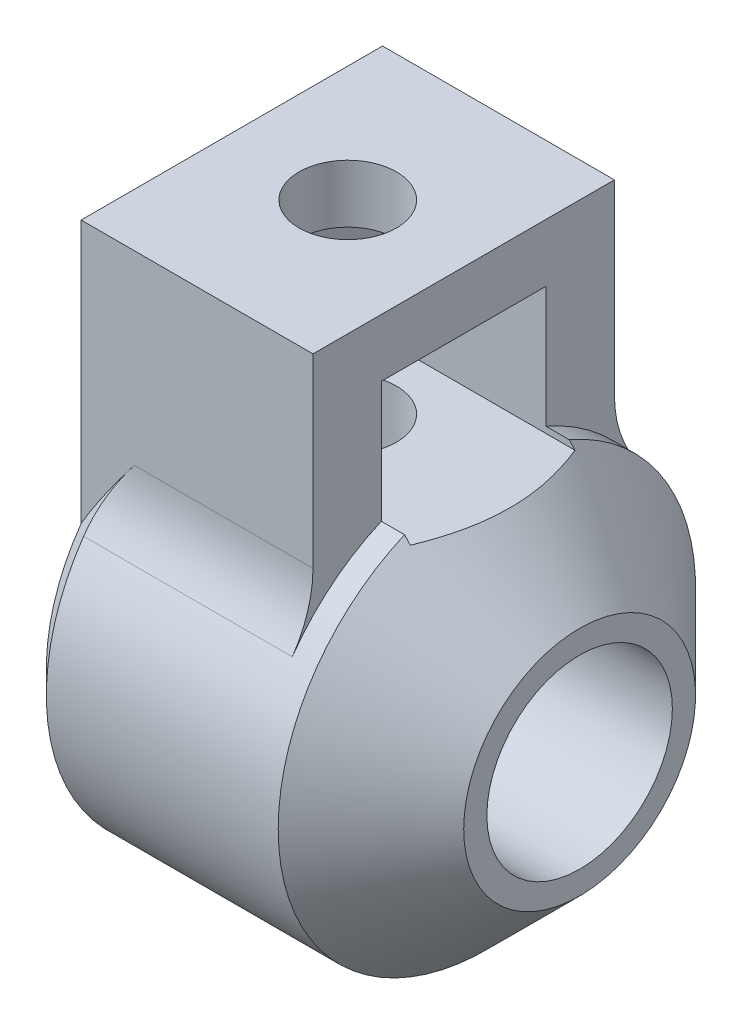
SolidWorks part; units mm, degrees
material "3D printed plastic"
ref_plane "Front Plane" through (0, 0, 0) normal (0, 0, 1) x (1, 0, 0)
ref_plane "Top Plane" through (0, 0, 0) normal (0, 1, 0) x (1, 0, 0)
ref_plane "Right Plane" through (0, 0, 0) normal (1, 0, 0) x (0, 0, -1)
sketch "Sketch1" plane through (0, 0, 0) normal (0, 0, 1) x (1, 0, 0)
  line L0 (0, 0) -> (11.5617, 0) construction
  line L1 (0, 4) -> (15, 4)
  line L2 (15, 4) -> (15, 5)
  line L3 (15, 5) -> (11, 9)
  line L4 (11, 9) -> (1, 9)
  line L5 (1, 9) -> (0, 8)
  line L6 (0, 8) -> (0, 4)
  dimension "D1" = 8
  dimension "D2" = 18
  dimension "D3" = 10
  dimension "D4" = 45
  dimension "D5" = 1
  dimension "D6" = 15
revolve "Revolve1" add sketch "Sketch1" angle 360 about L0
sketch "Sketch2" plane through (0, 0, 0) normal (-1, 0, 0) x (0, 0, 1)
  line L0 (0, 16) -> (0, 0) construction
  line L1 (-6.5, 4) -> (6.5, 4)
  line L2 (-6.5, 4) -> (-6.5, 16)
  line L3 (-6.5, 16) -> (6.5, 16)
  line L4 (6.5, 4) -> (6.5, 16)
  circle A0 centre (0, 0) radius 4 construction
  dimension "D1" = 13
  dimension "D2" = 12
extrude "Boss-Extrude1" add sketch "Sketch2" against normal blind 10
sketch "Sketch3" plane through (0, 16, 0) normal (0, 1, 0) x (1, 0, 0)
  line L0 (0, 0) -> (5, 0) construction
  line L1 (0, -6.5) -> (0, 6.5) construction
  line L2 (5, 0) -> (10, 0) construction
  line L3 (10, -6.5) -> (10, 6.5) construction
  circle A0 centre (5, 0) radius 2.1
  dimension "D1" = 4.2
extrude "Cut-Extrude1" cut sketch "Sketch3" against normal up to next
sketch "Sketch4" plane through (0, 16, 0) normal (0, 1, 0) x (1, 0, 0)
  line L0 (7.0496, 3.55) -> (15, 3.55)
  line L1 (7.0496, 3.55) -> (2.9504, 3.55)
  line L2 (2.9504, 3.55) -> (0.9008, 0)
  line L3 (0.9008, 0) -> (2.9504, -3.55)
  line L4 (2.9504, -3.55) -> (7.0496, -3.55)
  line L5 (7.0496, -3.55) -> (9.0992, 0) construction
  line L6 (9.0992, 0) -> (7.0496, 3.55) construction
  line L7 (15, 3.55) -> (15, -3.55)
  line L8 (15, -3.55) -> (7.0496, -3.55)
  line L10 (15, -5) -> (15, 5) construction
  circle A0 centre (5, 0) radius 3.55 construction
  dimension "D1" = 7.1
extrude "Cut-Extrude2" cut sketch "Sketch4" against normal blind 5.5 from offset 2.5 offset against normal yes
fillet "Fillet1" radius 5 2 edges at (5.5, 6.2249, -6.5) (5.5, 6.2249, 6.5)
